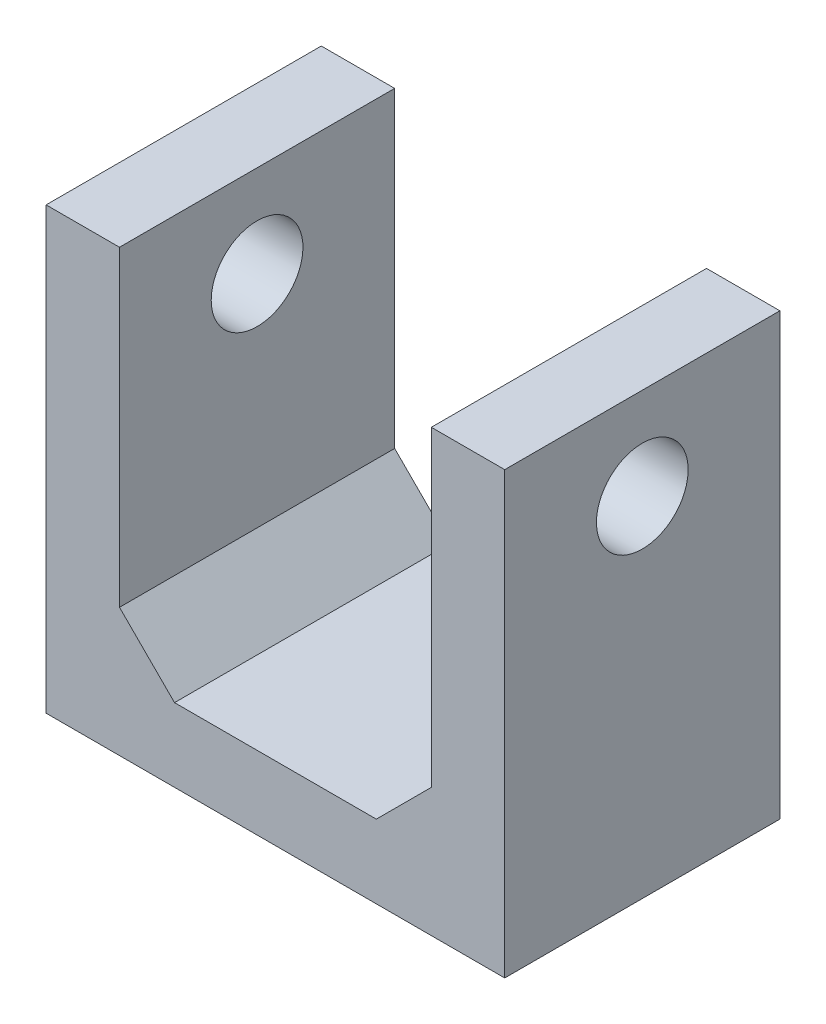
SolidWorks part; units mm, degrees
ref_plane "Płaszczyzna przednia" through (0, 0, 0) normal (0, 0, 1) x (1, 0, 0)
ref_plane "Płaszczyzna górna" through (0, 0, 0) normal (0, 1, 0) x (1, 0, 0)
ref_plane "Płaszczyzna prawa" through (0, 0, 0) normal (1, 0, 0) x (0, 0, -1)
sketch "Sketch1" plane through (0, 0, 0) normal (0, 0, 1) x (1, 0, 0)
  line L0 (-12.8821, 6.2493) -> (-12.8821, -17.7507)
  line L1 (-8.8821, 6.2493) -> (8.1179, 6.2493)
  line L2 (-8.8821, 6.2493) -> (-8.8821, -13.7507)
  line L3 (-8.8821, -13.7507) -> (8.1179, -13.7507)
  line L4 (8.1179, 6.2493) -> (8.1179, -13.7507)
  line L5 (-12.8821, -17.7507) -> (12.1179, -17.7507)
  line L6 (12.1179, 6.2493) -> (12.1179, -17.7507)
  line L7 (-12.8821, 6.2493) -> (-8.8821, 6.2493)
  line L8 (8.1179, 6.2493) -> (12.1179, 6.2493)
  dimension "D1" = 17
  dimension "D2" = 20
  dimension "D3" = 4
extrude "Boss-Extrude1" add sketch "Sketch1" along normal blind 15 contours L8 L4 L3 L2 L7 L0 L5 L6
chamfer "Chamfer1" distance 3 angle 45 1 edges at (-8.8821, -13.7507, 7.5)
chamfer "Chamfer2" distance 3 angle 45 1 edges at (8.1179, -13.7507, 7.5)
sketch "Sketch2" plane through (-12.8821, 0, 0) normal (-1, 0, 0) x (0, 0, 1)
  line L0 (15, 6.2493) -> (0, 6.2493) construction
  line L1 (0, 1.2493) -> (15, 1.2493) construction
  line L2 (0, 6.2493) -> (0, -17.7507) construction
  line L3 (15, 6.2493) -> (15, -17.7507) construction
  circle A0 centre (7.5, 1.2493) radius 2.5
  point P10 (7.5, 1.2493)
  dimension "D1" = 5
  dimension "D2" = 5
extrude "Cut-Extrude1" cut sketch "Sketch2" against normal blind 37
sketch "Sketch3" plane through (0, -17.7507, 0) normal (0, -1, 0) x (1, 0, 0)
  line L0 (-12.8821, 7.5) -> (12.1179, 7.5) construction
  line L1 (-0.3821, 15) -> (-0.3821, 0) construction
  line L2 (-12.8821, 15) -> (-12.8821, 0) construction
  line L3 (12.1179, 15) -> (12.1179, 0) construction
  line L4 (-12.8821, 15) -> (12.1179, 15) construction
  line L5 (-12.8821, 0) -> (12.1179, 0) construction
  circle A0 centre (-9.8821, 12) radius 1.5
  circle A1 centre (-9.8821, 3) radius 1.5
  circle A2 centre (9.1179, 12) radius 1.5
  circle A3 centre (9.1179, 3) radius 1.5
  point P14 (0, 0)
  dimension "D1" = 3
  dimension "D2" = 3
  dimension "D3" = 3
extrude "Cut-Extrude2" cut sketch "Sketch3" against normal blind 6
